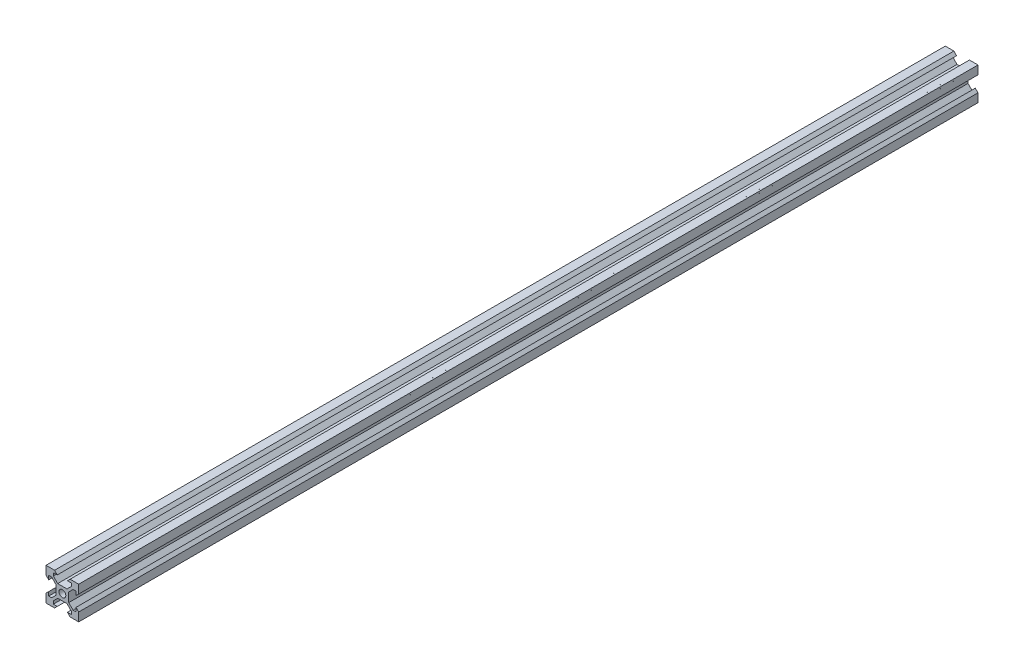
SolidWorks part; units mm, degrees
material "6061-T6 (SS)"
ref_plane "Front Plane" through (0, 0, 0) normal (0, 0, 1) x (1, 0, 0)
ref_plane "Top Plane" through (0, 0, 0) normal (0, 1, 0) x (1, 0, 0)
ref_plane "Right Plane" through (0, 0, 0) normal (1, 0, 0) x (0, 0, -1)
sketch "Sketch1" plane through (0, 0, 0) normal (0, 0, 1) x (1, 0, 0)
  line L0 (2.8343, 3.894) -> (5.5, 6.5588)
  line L1 (2.8343, -3.894) -> (-2.8343, -3.894)
  line L2 (3.8948, -2.8332) -> (3.8948, 2.8332)
  line L3 (2.8343, 3.894) -> (-2.8343, 3.894)
  line L4 (-3.8948, -2.8332) -> (-3.8948, 2.8332)
  line L5 (3.8994, -3.9006) -> (-3.8994, 3.9006) construction
  line L6 (3.9006, 3.8994) -> (-3.9006, -3.8994) construction
  line L7 (10, 4.747) -> (10, 9.9986)
  line L8 (5.5, 6.5588) -> (5.5, 8.3491)
  line L9 (5.5, 8.3491) -> (3.1, 8.3491)
  line L10 (3.1, 8.3491) -> (4.75, 9.9986)
  line L11 (4.75, 9.9986) -> (10, 9.9986)
  line L12 (8.35, 3.0975) -> (10, 4.747)
  line L13 (8.3507, 5.4975) -> (8.35, 3.0975)
  line L14 (6.5605, 5.498) -> (8.3507, 5.4975)
  line L15 (3.8948, 2.8332) -> (6.5605, 5.498)
  line L16 (0, -55) -> (0, 55) construction
  line L17 (-3.8948, 2.8332) -> (-6.5605, 5.498)
  line L18 (-6.5605, 5.498) -> (-8.3507, 5.4975)
  line L19 (-8.3507, 5.4975) -> (-8.35, 3.0975)
  line L20 (-8.35, 3.0975) -> (-10, 4.747)
  line L21 (-4.75, 9.9986) -> (-10, 9.9986)
  line L22 (-3.1, 8.3491) -> (-4.75, 9.9986)
  line L23 (-5.5, 8.3491) -> (-3.1, 8.3491)
  line L24 (-5.5, 6.5588) -> (-5.5, 8.3491)
  line L25 (-10, 4.747) -> (-10, 9.9986)
  line L26 (-2.8343, 3.894) -> (-5.5, 6.5588)
  line L27 (55, 0) -> (-55, 0) construction
  line L28 (3.8948, -2.8332) -> (6.5605, -5.498)
  line L29 (2.8343, -3.894) -> (5.5, -6.5588)
  line L30 (-3.8948, -2.8332) -> (-6.5605, -5.498)
  line L31 (-2.8343, -3.894) -> (-5.5, -6.5588)
  line L32 (-8.3507, -5.4975) -> (-8.35, -3.0975)
  line L33 (-8.35, -3.0975) -> (-10, -4.747)
  line L34 (8.3507, -5.4975) -> (8.35, -3.0975)
  line L35 (8.35, -3.0975) -> (10, -4.747)
  line L36 (-10, -4.747) -> (-10, -9.9986)
  line L37 (-5.5, -6.5588) -> (-5.5, -8.3491)
  line L38 (-5.5, -8.3491) -> (-3.1, -8.3491)
  line L39 (-3.1, -8.3491) -> (-4.75, -9.9986)
  line L40 (-4.75, -9.9986) -> (-10, -9.9986)
  line L41 (-6.5605, -5.498) -> (-8.3507, -5.4975)
  line L42 (6.5605, -5.498) -> (8.3507, -5.4975)
  line L43 (4.75, -9.9986) -> (10, -9.9986)
  line L44 (3.1, -8.3491) -> (4.75, -9.9986)
  line L45 (5.5, -8.3491) -> (3.1, -8.3491)
  line L46 (5.5, -6.5588) -> (5.5, -8.3491)
  line L47 (10, -4.747) -> (10, -9.9986)
  circle A0 centre (0, 0) radius 2.1
  point P0 (0, 0)
  dimension "D6" = 4.2
  dimension "D1" = 7.8
  dimension "D2" = 20
  dimension "D3" = 11
  dimension "D4" = 9.5
  dimension "D5" = 6.2
  dimension "D7" = 1.5
extrude "Boss-Extrude1" add sketch "Sketch1" along normal blind 550
